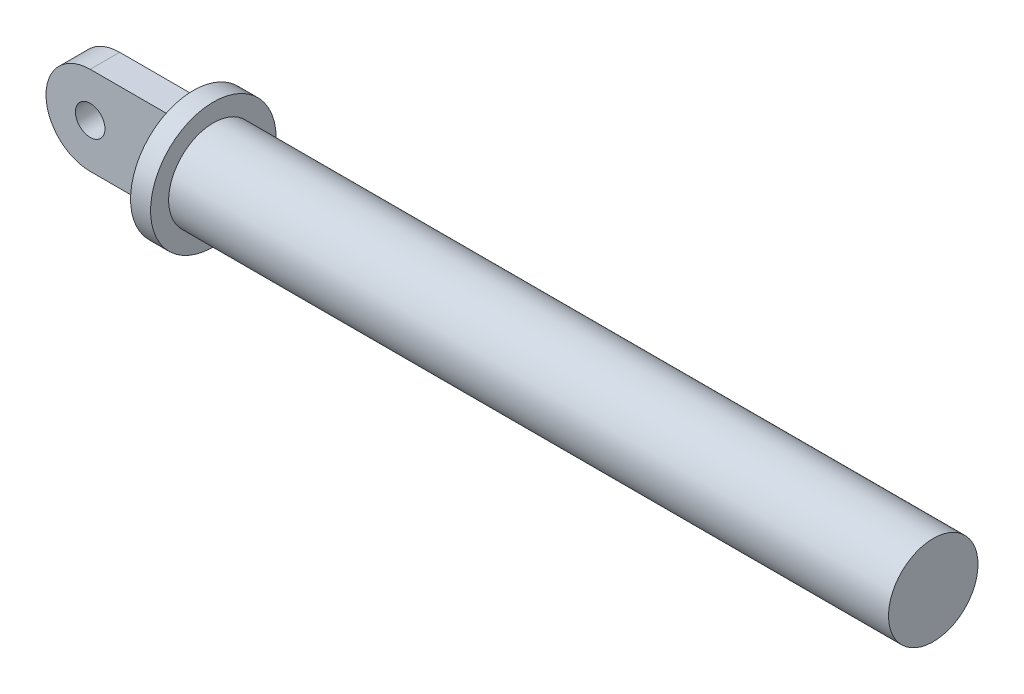
SolidWorks part; units mm, degrees
ref_plane "Front Plane" through (0, 0, 0) normal (0, 0, 1) x (1, 0, 0)
ref_plane "Top Plane" through (0, 0, 0) normal (0, 1, 0) x (1, 0, 0)
ref_plane "Right Plane" through (0, 0, 0) normal (1, 0, 0) x (0, 0, -1)
sketch "Sketch1" plane through (0, 0, 0) normal (0, 0, 1) x (1, 0, 0)
  line L1 (-52.4189, 39.0177) -> (-22.4189, 39.0177)
  line L3 (-52.4189, 9.0177) -> (-22.4189, 9.0177)
  line L4 (-22.4189, 39.0177) -> (-22.4189, 9.0177)
  circle A0 centre (-52.4189, 24.0177) radius 5.0037
  arc A1 (-52.4189, 39.0177) -> (-52.4189, 9.0177) centre (-52.4189, 24.0177) ccw
  dimension "D1" = 30
  dimension "D2" = 30
extrude "Boss-Extrude1" add sketch "Sketch1" along normal mid plane 10
sketch "Sketch2" plane through (0, 0, 0) normal (0, 0, 1) x (1, 0, 0)
  line L0 (-22.4189, 24.0177) -> (-22.4189, 45.3243)
  line L1 (-22.4189, 9.0177) -> (-22.4189, 39.0177) construction
  line L2 (-22.4189, 45.3243) -> (-15.6234, 45.3243)
  line L3 (-15.6234, 45.3243) -> (-15.6234, 39.1949)
  line L4 (-15.6234, 39.1949) -> (228.6339, 39.1949)
  line L5 (228.6339, 39.1949) -> (228.6339, 24.0177)
  line L6 (228.6339, 24.0177) -> (-22.4189, 24.0177)
revolve "Revolve4" add sketch "Sketch2" angle 360 about L6
